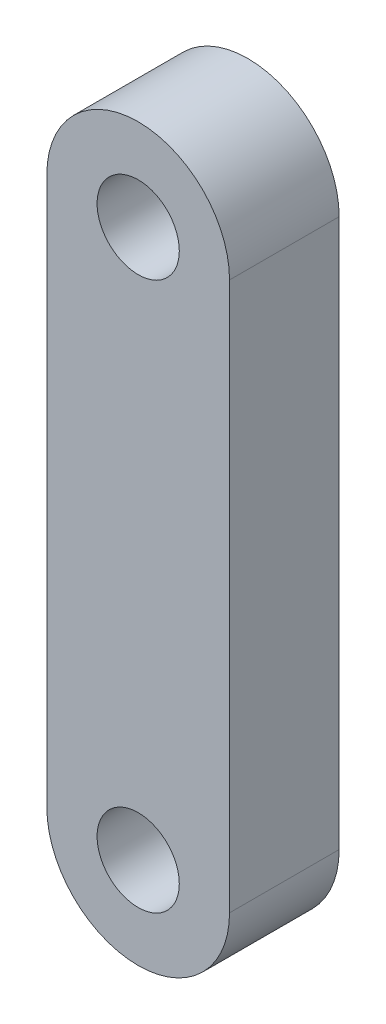
SolidWorks part; units mm, degrees
material "6061-T6 (SS)"
ref_plane "Alzado" through (0, 0, 0) normal (0, 0, 1) x (1, 0, 0)
ref_plane "Planta" through (0, 0, 0) normal (0, 1, 0) x (1, 0, 0)
ref_plane "Vista lateral" through (0, 0, 0) normal (1, 0, 0) x (0, 0, -1)
sketch "Croquis1" plane through (0, 0, 0) normal (0, 0, 1) x (1, 0, 0)
  line L0 (0, -15) -> (0, 15) construction
  line L1 (-5, -15) -> (-5, 15)
  line L2 (5, -15) -> (5, 15)
  arc A0 (-5, -15) -> (5, -15) centre (0, -15) ccw
  arc A1 (5, 15) -> (-5, 15) centre (0, 15) ccw
  point P3 (0, 0)
  dimension "D1" = 30
  dimension "D2" = 10
extrude "Saliente-Extruir1" add sketch "Croquis1" along normal mid plane 6
hole_wizard "Taladro de margen para M41" positions "Croquis2" profile "Croquis3" hole size "M4" standard "Ansi Metric" end condition up to next
sketch "Croquis2" plane through (0, 0, 3) normal (0, 0, 1) x (1, 0, 0)
  point P0 (0, 15)
  point P3 (0, -15)
sketch "Croquis3" plane through (0, 15, 3) normal (1, 0, 0) x (0, -1, 0)
  line L0 (0, 0) -> (0, 6)
  line L1 (0, 6) -> (2.25, 6)
  line L2 (2.25, 6) -> (2.25, 0)
  line L5 (2.25, 0) -> (0, 0)
  line L11 (0, -6.35) -> (0, 107.95) construction
  dimension "Diámetro de taladro hasta el siguiente" = 4.5
  dimension "Profundidad de taladro hasta el siguiente" = 6
hole_wizard "Taladro de margen para M42" positions "Croquis4" profile "Croquis5" hole size "M4" standard "Ansi Metric"
sketch "Croquis4" plane through (0, 0, 3) normal (0, 0, 1) x (1, 0, 0)
  circle A0 centre (0, -15) radius 2.25 construction
  point P0 (0, -8.5)
  dimension "D1" = 6.5
sketch "Croquis5" plane through (0, -8.5, 3) normal (1, 0, 0) x (0, -1, 0)
  line L0 (0, 0) -> (0, 6)
  line L1 (0, 6) -> (2.25, 6)
  line L2 (2.25, 6) -> (2.25, 0)
  line L5 (2.25, 0) -> (0, 0)
  line L11 (0, -6.35) -> (0, 107.95) construction
  dimension "Diámetro de taladro hasta el siguiente" = 4.5
  dimension "Profundidad de taladro hasta el siguiente" = 6
